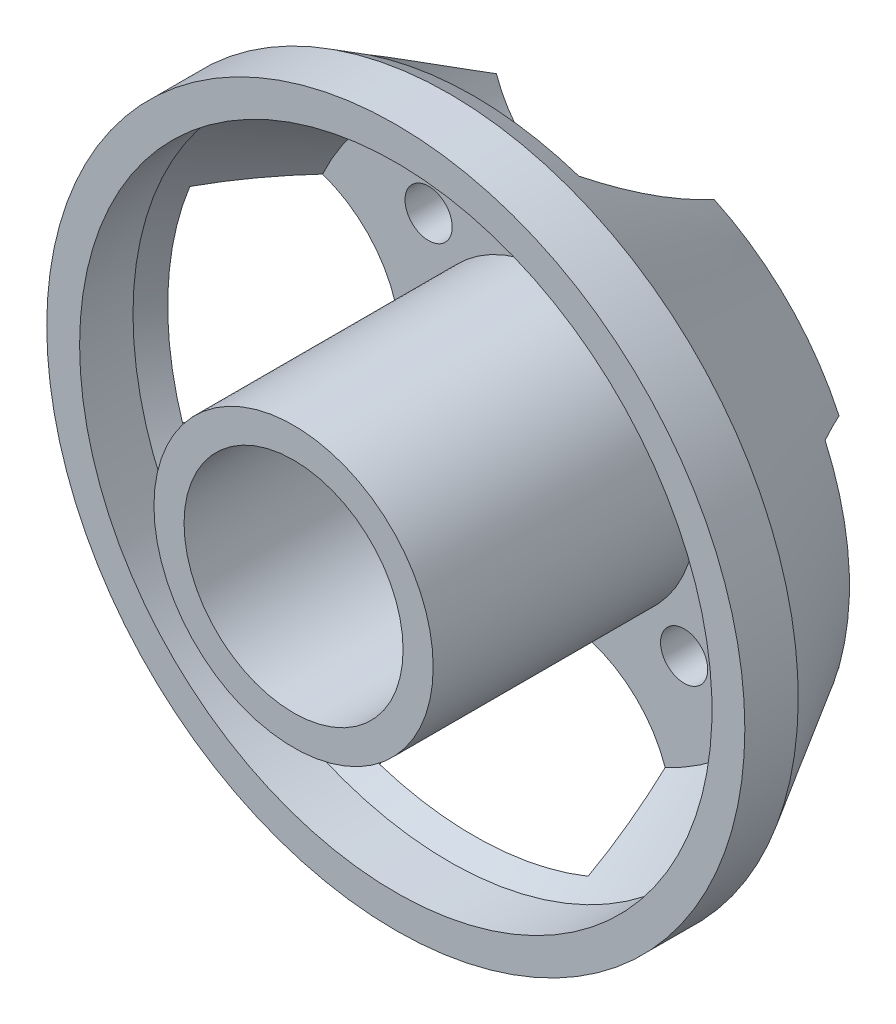
SolidWorks part; units mm, degrees
ref_plane "Front Plane" through (0, 0, 0) normal (0, 0, 1) x (1, 0, 0)
ref_plane "Top Plane" through (0, 0, 0) normal (0, 1, 0) x (1, 0, 0)
ref_plane "Right Plane" through (0, 0, 0) normal (1, 0, 0) x (0, 0, -1)
sketch "Sketch1" plane through (0, 0, 0) normal (0, 0, 1) x (1, 0, 0)
  circle A2 centre (0, 0) radius 19.25
  circle A3 centre (0, 0) radius 21.25
  circle A4 centre (0, 0) radius 19.25 construction
  circle A5 centre (0, 0) radius 21.25 construction
  point P7 (0, 0)
extrude "Boss-Extrude1" add sketch "Sketch1" along normal blind 3.25
sketch "Sketch2" plane through (0, 0, 0) normal (0, 1, 0) x (1, 0, 0)
  line L0 (-21.25, 0) -> (-15.7, 9.5)
  line L1 (15.7, 9.5) -> (-15.7, 9.5) construction
  line L3 (21.25, 0) -> (-21.25, 0) construction
  line L4 (-15.7, 6.5264) -> (-19.5128, 0)
  line L5 (-15.7, 6.5264) -> (0, 6.5264)
  line L7 (-21.25, 0) -> (-19.5128, 0)
  line L8 (-15.7, 9.5) -> (0, 9.5)
  line L9 (0, 9.5) -> (0, 6.5264)
  point P6 (0, 9.5)
  dimension "D1" = 31.4
  dimension "D2" = 9.5
  dimension "D3" = 1.5
revolve "Revolve1" add sketch "Sketch2" angle 360 about L9
sketch "Sketch4" plane through (0, 0, -9.5) normal (0, 0, -1) x (-1, 0, 0)
  line L0 (-9.5, 0) -> (9.5, 0) construction
  line L1 (0, -9.5) -> (0, 9.5) construction
  circle A0 centre (0, 16.5) radius 7
  circle A1 centre (16.5, 0) radius 7
  circle A2 centre (0, -16.5) radius 7
  circle A4 centre (-16.5, 0) radius 7 [skipped]
  point P3 (0, 0)
  point P4 (0, 0)
  point P8 (0, 0)
  point P10 (0, -16.5)
  point P18 (0, 0)
  circle M3 centre (0, 0) radius 15.7
  dimension "D3" = 14
  dimension "D1" = 19
  dimension "D2" = 19
  dimension "D4" = 4
extrude "Cut-Extrude2" cut sketch "Sketch4" against normal blind 8 contours A1 M3 | A1 M3 | A2 M3 | A2 M3 | A0
sketch "Sketch5" plane through (0, 0, -9.5) normal (0, 0, -1) x (-1, 0, 0)
  line L0 (9.5, 0) -> (-9.5, 0) construction
  arc A0 (14.2345, 6.6233) -> (14.2345, -6.6233) centre (16.5, 0) ccw construction
  circle A1 centre (-16.5, 0) radius 7
  point P9 (0, 0)
  dimension "D2" = 14
  dimension "D1" = 19
extrude "Cut-Extrude3" cut sketch "Sketch5" against normal blind 2
sketch "Sketch6" plane through (0, 0, -9.5) normal (0, 0, -1) x (-1, 0, 0)
  circle A0 centre (0, 0) radius 6.6675
  dimension "D1" = 13.335
sketch "Sketch7" plane through (0, 0, -6.5264) normal (0, 0, 1) x (1, 0, 0)
  circle A0 centre (0, 0) radius 8.5
  dimension "D1" = 17
extrude "Boss-Extrude2" add sketch "Sketch7" along normal blind 16
extrude "Cut-Extrude5" cut sketch "Sketch6" against normal through all
sketch "Sketch8" plane through (0, 0, -9.5) normal (0, 0, -1) x (-1, 0, 0)
  circle A0 centre (0, 0) radius 2.3813
  circle A1 centre (0, 0) radius 6.6675 construction
  circle A2 centre (0, 0) radius 6.6675
  dimension "D1" = 4.7625
hole_wizard "#33 (0.113) Diameter Hole1" positions "Sketch9" profile "Sketch10" hole size "#33" standard "ANSI Inch" end condition through all
sketch "Sketch9" plane through (0, 0, -9.5) normal (0, 0, -1) x (-1, 0, 0)
  line L0 (-7.7782, 7.7782) -> (7.7782, -7.7782) construction
  line L2 (-7.7782, -7.7782) -> (7.7782, 7.7782) construction
  line L4 (0, 0) -> (0, -6.6675) construction
  circle A0 centre (0, 0) radius 6.6675 construction
  point P0 (7.7782, 7.7782)
  point P2 (7.7782, -7.7782)
  point P4 (-7.7782, -7.7782)
  point P6 (-7.7782, 7.7782)
  dimension "D1" = 90
  dimension "D2" = 11
  dimension "D3" = 45
sketch "Sketch10" plane through (-7.7782, 7.7782, -9.5) normal (1, 0, 0) x (0, 1, 0)
  line L0 (0, 0) -> (0, 18.9736)
  line L1 (0, 18.9736) -> (1.4351, 18.9736)
  line L2 (1.4351, 18.9736) -> (1.4351, 0)
  line L5 (1.4351, 0) -> (0, 0)
  line L11 (0, -6.35) -> (0, 107.95) construction
  dimension "Thru Hole Dia." = 2.8702
  dimension "Thru Hole Depth" = 18.9736
